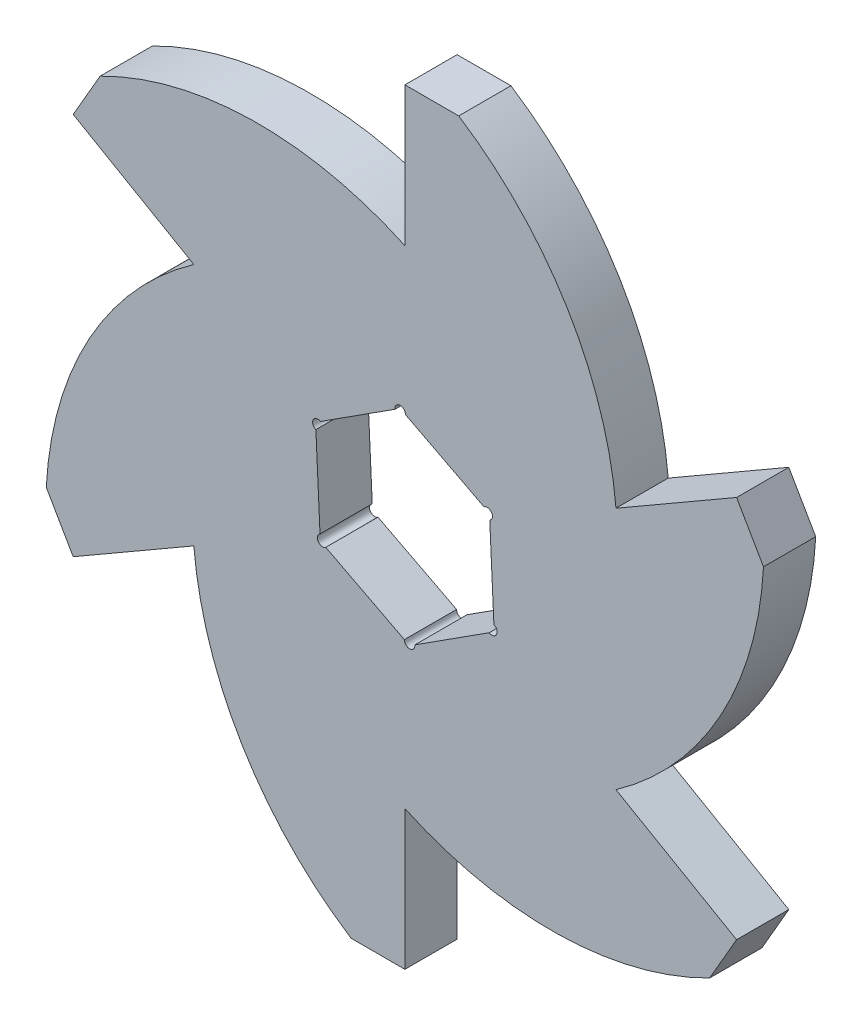
SolidWorks part; units mm, degrees
ref_plane "Front Plane" through (0, 0, 0) normal (0, 0, 1) x (1, 0, 0)
ref_plane "Top Plane" through (0, 0, 0) normal (0, 1, 0) x (1, 0, 0)
ref_plane "Right Plane" through (0, 0, 0) normal (1, 0, 0) x (0, 0, -1)
sketch "Sketch1" plane through (0, 0, 0) normal (0, 0, 1) x (1, 0, 0)
  line L0 (0, 0) -> (0, 119.732) construction
  line L1 (-2.8394, 27.8822) -> (-24.2285, 14.1575)
  line L2 (-25.5664, 11.4821) -> (-24.375, -13.9038)
  line L3 (-22.727, -16.4001) -> (-0.1465, -28.0612)
  line L4 (2.8394, -27.8822) -> (24.2285, -14.1575)
  line L5 (25.5664, -11.4821) -> (24.375, 13.9038)
  line L6 (22.727, 16.4001) -> (0.1465, 28.0612)
  line L7 (0, 0) -> (16.961, 120.6838) construction
  line L8 (0, 0) -> (103.6909, 59.866) construction
  line L9 (0, 0) -> (112.9957, 45.6532) construction
  line L10 (0, 0) -> (103.6909, -59.866) construction
  line L11 (0, 0) -> (96.0347, -75.0306) construction
  line L12 (0, 0) -> (0, -119.732) construction
  line L13 (0, 0) -> (-16.961, -120.6838) construction
  line L14 (0, 0) -> (-103.6909, -59.866) construction
  line L15 (0, 0) -> (-112.9957, -45.6532) construction
  line L16 (0, 0) -> (-103.6909, 59.866) construction
  line L17 (0, 0) -> (-96.0347, 75.0306) construction
  line L18 (0, 70) -> (0, 110)
  line L19 (0, 110) -> (15.4595, 110)
  line L20 (60.6218, 35) -> (95.2628, 55)
  line L21 (95.2628, 55) -> (102.9925, 41.6117)
  line L22 (60.6218, -35) -> (95.2628, -55)
  line L23 (95.2628, -55) -> (87.533, -68.3883)
  line L24 (0, -70) -> (0, -110)
  line L25 (0, -110) -> (-15.4595, -110)
  line L26 (-60.6218, -35) -> (-95.2628, -55)
  line L27 (-95.2628, -55) -> (-102.9925, -41.6117)
  line L28 (-60.6218, 35) -> (-95.2628, 55)
  line L29 (-95.2628, 55) -> (-87.533, 68.3883)
  circle A0 centre (0, 0) radius 25 construction
  arc A1 (0.1465, 28.0612) -> (-2.8394, 27.8822) centre (-1.3533, 28.0858) ccw
  arc A2 (24.375, 13.9038) -> (22.727, 16.4001) centre (23.6463, 15.2149) ccw
  arc A3 (24.2285, -14.1575) -> (25.5664, -11.4821) centre (24.9996, -12.8709) ccw
  arc A4 (-0.1465, -28.0612) -> (2.8394, -27.8822) centre (1.3533, -28.0858) ccw
  arc A5 (-24.375, -13.9038) -> (-22.727, -16.4001) centre (-23.6463, -15.2149) ccw
  arc A6 (-24.2285, 14.1575) -> (-25.5664, 11.4821) centre (-24.9996, 12.8709) ccw
  circle A7 centre (0, 0) radius 70 construction
  arc A8 (15.4595, 110) -> (60.6218, 35) centre (-38.9831, 26.1191) cw
  arc A9 (102.9925, 41.6117) -> (60.6218, -35) centre (3.1283, 46.8199) cw
  arc A10 (87.533, -68.3883) -> (0, -70) centre (42.1113, 20.7008) cw
  arc A11 (-15.4595, -110) -> (-60.6218, -35) centre (38.9831, -26.1191) cw
  arc A12 (-102.9925, -41.6117) -> (-60.6218, 35) centre (-3.1283, -46.8199) cw
  arc A13 (-87.533, 68.3883) -> (0, 70) centre (-42.1113, -20.7008) cw
  point P24 (0, 0)
  point P38 (0, 0)
  point P69 (0, 0)
  dimension "D1" = 50
  dimension "D3" = 3
  dimension "D2" = 140
  dimension "D8" = 100
  dimension "D5" = 8
  dimension "D7" = 40
  dimension "D4" = 6
  dimension "D6" = 6
  dimension "D9" = 6
extrude "Boss-Extrude1" add sketch "Sketch1" along normal blind 15
